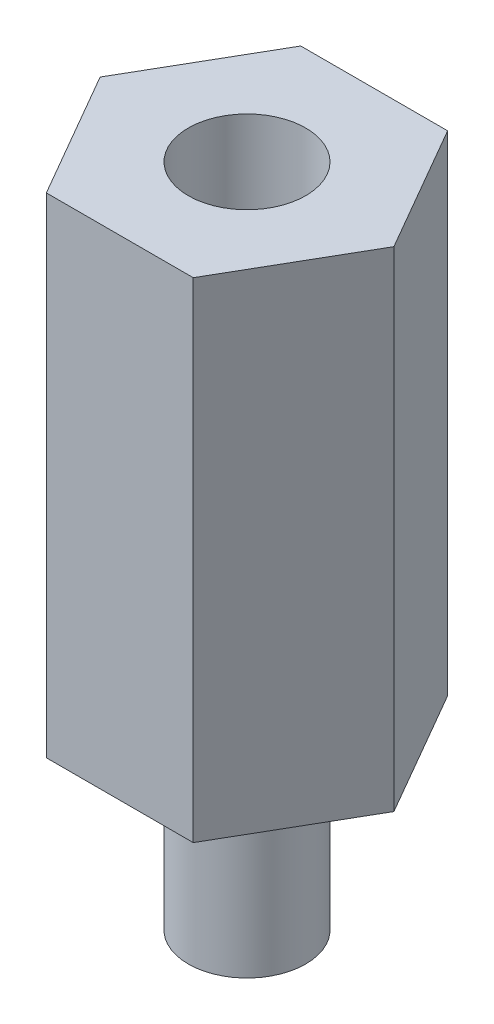
SolidWorks part; units mm, degrees
ref_plane "Front Plane" through (0, 0, 0) normal (0, 0, 1) x (1, 0, 0)
ref_plane "Top Plane" through (0, 0, 0) normal (0, 1, 0) x (1, 0, 0)
ref_plane "Right Plane" through (0, 0, 0) normal (1, 0, 0) x (0, 0, -1)
sketch "Sketch1" plane through (0, 0, 0) normal (0, 1, 0) x (1, 0, 0)
  line L1 (7.5056, 0) -> (3.7528, 6.5)
  line L2 (3.7528, 6.5) -> (-3.7528, 6.5)
  line L3 (-3.7528, 6.5) -> (-7.5056, 0)
  line L4 (-7.5056, 0) -> (-3.7528, -6.5)
  line L5 (-3.7528, -6.5) -> (3.7528, -6.5)
  line L6 (3.7528, -6.5) -> (7.5056, 0)
  circle A0 centre (0, 0) radius 6.5 construction
extrude "Boss-Extrude1" add sketch "Sketch1" along normal blind 25
sketch "Sketch2" plane through (0, 0, 0) normal (0, -1, 0) x (1, 0, 0)
  circle A0 centre (0, 0) radius 3
  dimension "D1" = 6
extrude "Boss-Extrude2" add sketch "Sketch2" along normal blind 9
hole_wizard "Ø6.0mm Dowel Hole1" positions "Sketch4" profile "Sketch5" hole size "Ø6.0" standard "ANSI Metric"
sketch "Sketch4" plane through (0, 25, 0) normal (0, 1, 0) x (1, 0, 0)
  point P0 (0, 0)
sketch "Sketch5" plane through (0, 25, 0) normal (1, 0, 0) x (0, 0, 1)
  line L0 (0, 0) -> (0, 10.8026)
  line L1 (0, 10.8026) -> (3, 9)
  line L2 (3, 9) -> (3, 0)
  line L5 (3, 0) -> (0, 0)
  line L10 (0, 10.8026) -> (-3, 9) construction
  line L11 (0, -6.35) -> (0, 107.95) construction
  dimension "Hole Dia." = 6
  dimension "Hole Depth" = 9
  dimension "Drill Angle" = 118
